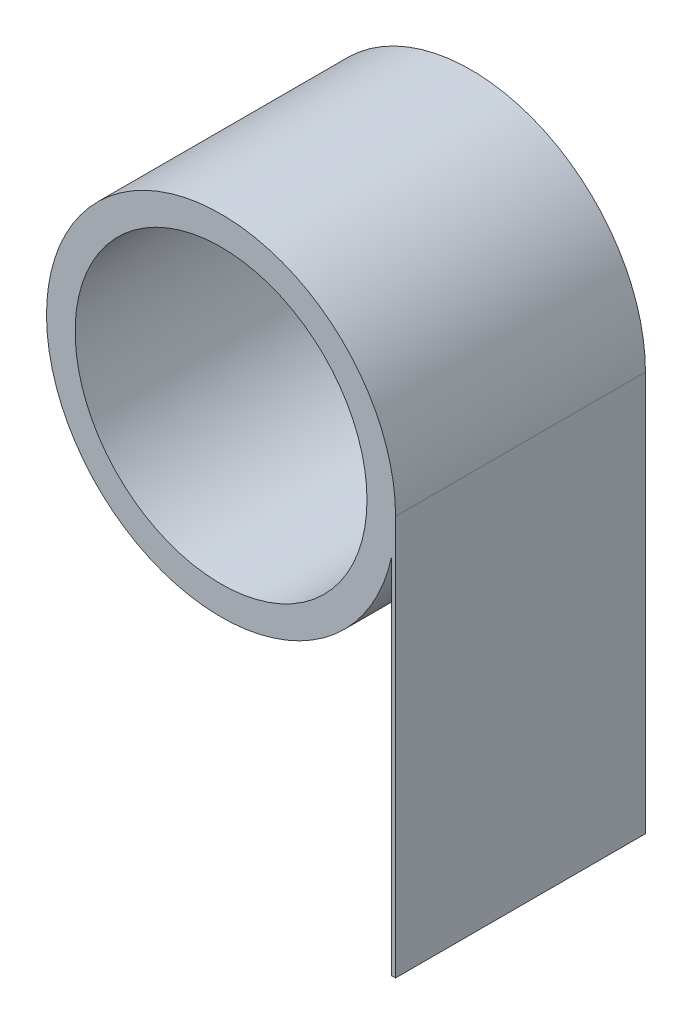
SolidWorks part; units mm, degrees
ref_plane "Front Plane" through (0, 0, 0) normal (0, 0, 1) x (1, 0, 0)
ref_plane "Top Plane" through (0, 0, 0) normal (0, 1, 0) x (1, 0, 0)
ref_plane "Right Plane" through (0, 0, 0) normal (1, 0, 0) x (0, 0, -1)
sketch "Sketch1" plane through (0, 0, 0) normal (0, 0, 1) x (1, 0, 0)
  circle A0 centre (0, 0) radius 9.271
  circle A1 centre (0, 0) radius 11.0871
  dimension "D1" = 22.1742
  dimension "D2" = 18.542
extrude "Boss-Extrude1" add sketch "Sketch1" along normal blind 15.875
sketch "Sketch2" plane through (0, 0, 15.875) normal (0, 0, 1) x (1, 0, 0)
  line L0 (11.0871, 0) -> (11.0871, -25.4)
  line L1 (11.0871, -25.4) -> (10.8331, -25.4)
  line L2 (10.8331, -25.4) -> (10.8331, -2.3596)
  circle A0 centre (0, 0) radius 11.0871 construction
  arc A1 (10.8331, -2.3596) -> (11.0871, 0) centre (0, 0) ccw
  point P4 (12.5531, -24.6922)
  dimension "D1" = 0.254
  dimension "D2" = 25.4
extrude "Boss-Extrude2" add sketch "Sketch2" against normal up to surface (15.875 mm away) up to face at (11.0871, 0, 0)
